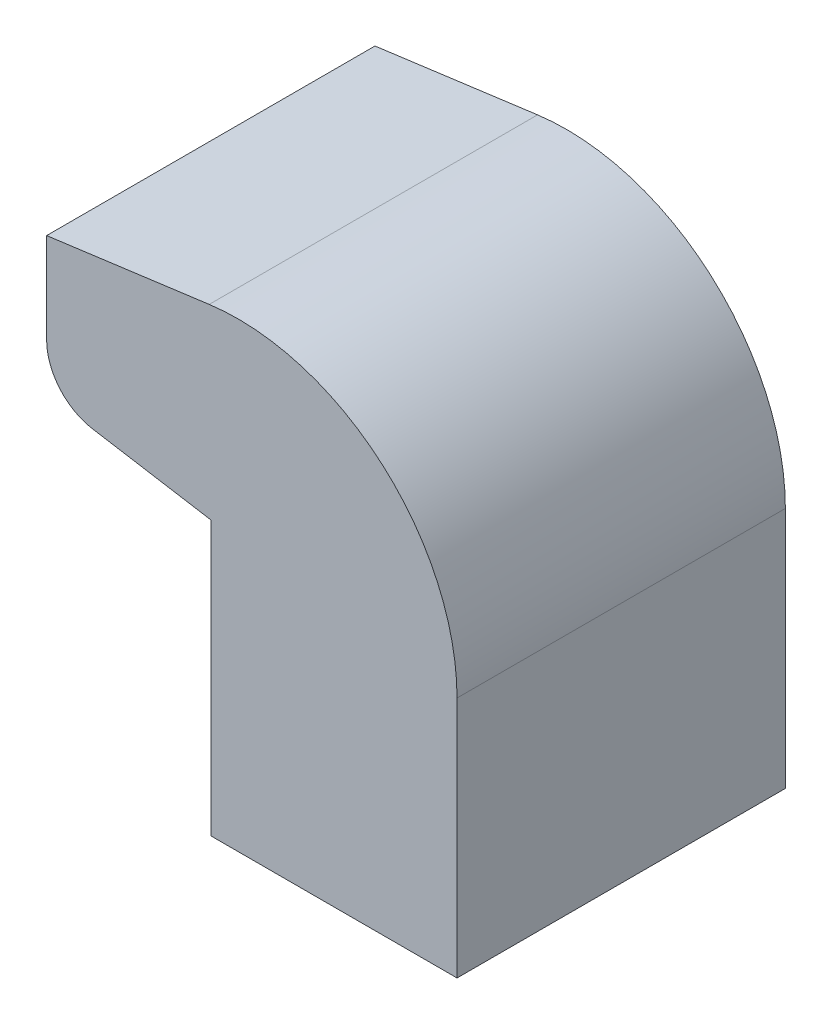
SolidWorks part; units mm, degrees
material "45"
ref_plane "前视基准面" through (0, 0, 0) normal (0, 0, 1) x (1, 0, 0)
ref_plane "上视基准面" through (0, 0, 0) normal (0, 1, 0) x (1, 0, 0)
ref_plane "右视基准面" through (0, 0, 0) normal (1, 0, 0) x (0, 0, -1)
sketch "草图1" plane through (0, 0, 0) normal (0, 0, 1) x (1, 0, 0)
  line L0 (0, 0) -> (0, 55)
  line L1 (0, 55) -> (-30, 60)
  line L2 (0, 0) -> (45, 0)
  line L3 (45, 0) -> (45, 49.3127)
  line L4 (-30, 60) -> (-30, 85)
  line L5 (-30, 85) -> (-0.2865, 88.9618)
  arc A1 (-0.2865, 88.9618) -> (45, 49.3127) centre (5, 49.3127) cw
  point P11 (45, 95)
  dimension "D1" = 45
  dimension "D6" = 95
  dimension "D7" = 40
  dimension "D2" = 75
  dimension "D3" = 55
  dimension "D4" = 25
  dimension "D5" = 85
extrude "凸台-拉伸1" add sketch "草图1" along normal mid plane 60
chamfer "倒角1" distance 5 angle 45 4 edges at (0, 0, 0) (22.5, 0, 30) (45, 0, 0) (22.5, 0, -30)
sketch "草图2" plane through (45, 0, 0) normal (1, 0, 0) x (0, 0, -1)
  line L0 (25, 0) -> (-25, 0) construction
  line L1 (-10, 0) -> (10, 0)
  line L2 (-10, 0) -> (-10, 30)
  line L3 (-10, 30) -> (10, 30)
  line L4 (10, 0) -> (10, 30)
  line L5 (0, 0) -> (0, 49.3127) construction
  line L6 (-30, 49.3127) -> (30, 49.3127) construction
  dimension "D1" = 20
  dimension "D2" = 30
extrude "切除-拉伸1" [suppressed] cut sketch "草图2" against normal through all
fillet "圆角1" radius 10 1 edges at (-30, 60, 0)
